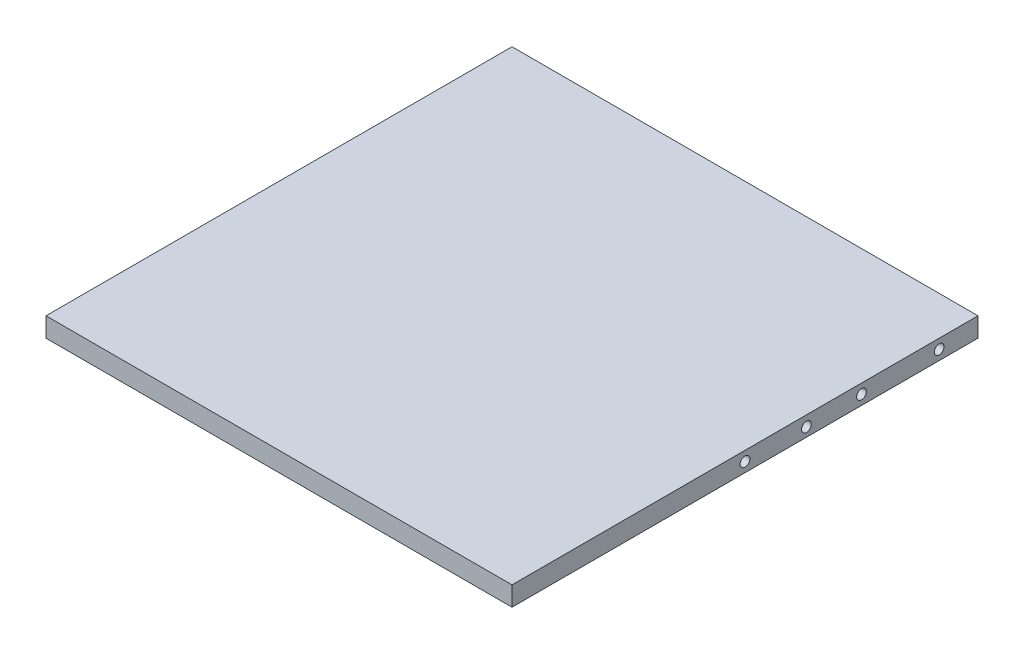
SolidWorks part; units mm, degrees
ref_plane "Front Plane" through (0, 0, 0) normal (0, 0, 1) x (1, 0, 0)
ref_plane "Top Plane" through (0, 0, 0) normal (0, 1, 0) x (1, 0, 0)
ref_plane "Right Plane" through (0, 0, 0) normal (1, 0, 0) x (0, 0, -1)
sketch "Sketch2" plane through (0, 0, 0) normal (0, 1, 0) x (1, 0, 0)
  line L1 (-250.732, 154.9522) -> (54.068, 154.9522)
  line L2 (-250.732, 154.9522) -> (-250.732, -149.8478)
  line L3 (-250.732, -149.8478) -> (54.068, -149.8478)
  line L4 (54.068, 154.9522) -> (54.068, -149.8478)
  dimension "D1" = 304.8
  dimension "D2" = 304.8
extrude "Boss-Extrude1" add sketch "Sketch2" along normal blind 12.7
sketch "Sketch3" plane through (54.068, 0, 0) normal (1, 0, 0) x (0, 0, -1)
  circle A0 centre (2.5522, 6.35) radius 3.175
  dimension "D1" = 6.35
extrude "Cut-Extrude1" cut sketch "Sketch3" against normal through all
sketch "Sketch4" plane through (-250.732, 0, 0) normal (-1, 0, 0) x (0, 0, 1)
  circle A0 centre (-42.7262, 5.8944) radius 3.175
extrude "Cut-Extrude2" cut sketch "Sketch4" against normal through all
sketch "Sketch5" plane through (-250.732, 0, 0) normal (-1, 0, 0) x (0, 0, 1)
  circle A0 centre (-78.7522, 6.35) radius 3.175
  circle A1 centre (-2.5522, 6.35) radius 3.175 construction
  dimension "D1" = 76.2
extrude "Cut-Extrude7" cut sketch "Sketch5" against normal through all both and the other way through all
sketch "Sketch6" plane through (-250.732, 0, 0) normal (-1, 0, 0) x (0, 0, 1)
  circle A0 centre (-129.5522, 6.35) radius 3.175
  circle A1 centre (-2.5522, 6.35) radius 3.175 construction
  dimension "D1" = 127
extrude "Cut-Extrude8" cut sketch "Sketch6" against normal through all both and the other way through all
scale "Scale1" scale about centroid uniform scaling yes scale factor 1.5
